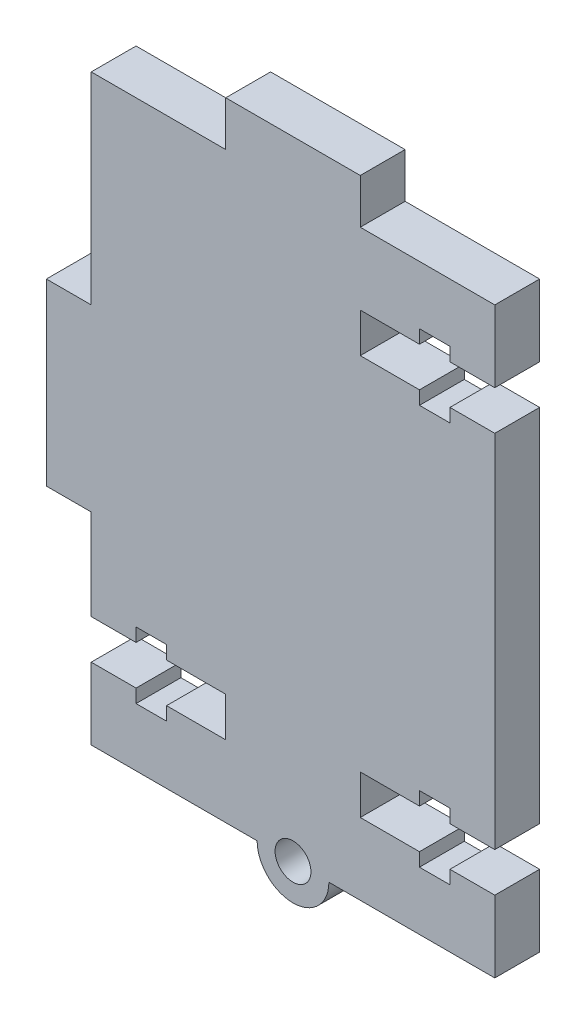
SolidWorks part; units mm, degrees
ref_plane "Front Plane" through (0, 0, 0) normal (0, 0, 1) x (1, 0, 0)
ref_plane "Top Plane" through (0, 0, 0) normal (0, 1, 0) x (1, 0, 0)
ref_plane "Right Plane" through (0, 0, 0) normal (1, 0, 0) x (0, 0, -1)
sketch "Sketch1" plane through (0, 0, 0) normal (0, 0, 1) x (1, 0, 0)
  line L0 (7.5, 32.5) -> (7.5, 37.5)
  line L1 (-22.5, 32.5) -> (-7.5, 32.5)
  line L2 (-22.5, 32.5) -> (-22.5, 10)
  line L3 (-22.5, -32.5) -> (22.5, -32.5)
  line L4 (22.5, 32.5) -> (22.5, -32.5)
  line L5 (7.5, 37.5) -> (-7.5, 37.5)
  line L6 (-7.5, 37.5) -> (-7.5, 32.5)
  line L7 (7.5, 32.5) -> (22.5, 32.5)
  line L8 (-22.5, -10) -> (-22.5, -32.5)
  line L9 (-22.5, 10) -> (-27.5, 10)
  line L11 (-22.5, -10) -> (-27.5, -10)
  line L12 (-27.5, 10) -> (-27.5, -10)
  point P13 (-25, 10)
  dimension "D1" = 45
  dimension "D2" = 65
  dimension "D3" = 22.5
  dimension "D4" = 32.5
  dimension "D5" = 15
  dimension "D6" = 15
  dimension "D7" = 5
  dimension "D8" = 5
  dimension "D9" = 22.5
  dimension "D10" = 20
extrude "Boss-Extrude1" add sketch "Sketch1" along normal blind 5
sketch "Sketch3" plane through (0, 0, 5) normal (0, 0, 1) x (1, 0, 0)
  line L0 (0, 0) -> (28.1265, 0) construction
  line L13 (22.5, -32.5) -> (22.5, 32.5) construction
  line L14 (22.5, 24.5) -> (17.5, 24.5)
  line L15 (17.5, 24.5) -> (17.5, 26)
  line L16 (17.5, 26) -> (14.1, 26)
  line L17 (14.1, 26) -> (14.1, 24.5)
  line L18 (14.1, 24.5) -> (7.5, 24.5)
  line L19 (7.5, 24.5) -> (7.5, 20.1)
  line L20 (7.5, 20.1) -> (14.1, 20.1)
  line L21 (14.1, 20.1) -> (14.1, 18.6)
  line L22 (14.1, 18.6) -> (17.5, 18.6)
  line L23 (17.5, 18.6) -> (17.5, 20.1)
  line L24 (17.5, 20.1) -> (22.5, 20.1)
  line L25 (22.5, 24.5) -> (22.5, 20.1)
  line L26 (-7.5, 32.5) -> (-22.5, 32.5) construction
  line L27 (0, 0) -> (0, 42.4523) construction
  line L28 (22.5, -24.5) -> (22.5, -20.1)
  line L29 (17.5, -20.1) -> (22.5, -20.1)
  line L30 (17.5, -18.6) -> (17.5, -20.1)
  line L31 (14.1, -18.6) -> (17.5, -18.6)
  line L32 (14.1, -20.1) -> (14.1, -18.6)
  line L33 (7.5, -20.1) -> (14.1, -20.1)
  line L34 (7.5, -24.5) -> (7.5, -20.1)
  line L35 (14.1, -24.5) -> (7.5, -24.5)
  line L36 (14.1, -26) -> (14.1, -24.5)
  line L37 (17.5, -26) -> (14.1, -26)
  line L38 (17.5, -24.5) -> (17.5, -26)
  line L39 (22.5, -24.5) -> (17.5, -24.5)
  line L40 (-22.5, -24.5) -> (-17.5, -24.5)
  line L41 (-17.5, -24.5) -> (-17.5, -26)
  line L42 (-17.5, -26) -> (-14.1, -26)
  line L43 (-14.1, -26) -> (-14.1, -24.5)
  line L44 (-14.1, -24.5) -> (-7.5, -24.5)
  line L45 (-7.5, -24.5) -> (-7.5, -20.1)
  line L46 (-7.5, -20.1) -> (-14.1, -20.1)
  line L47 (-14.1, -20.1) -> (-14.1, -18.6)
  line L48 (-14.1, -18.6) -> (-17.5, -18.6)
  line L49 (-17.5, -18.6) -> (-17.5, -20.1)
  line L50 (-17.5, -20.1) -> (-22.5, -20.1)
  line L51 (-22.5, -24.5) -> (-22.5, -20.1)
  dimension "D8" = 4.4
  dimension "D9" = 1.5
  dimension "D10" = 1.5
  dimension "D11" = 3.4
  dimension "D12" = 5
  dimension "D13" = 8
  dimension "D14" = 15
extrude "Cut-Extrude1" cut sketch "Sketch3" against normal blind 5
sketch "Sketch10" plane through (0, 0, 5) normal (0, 0, 1) x (1, 0, 0)
  line L0 (0, 0) -> (0, -37.4843) construction
  line L1 (-22.5, -32.5) -> (22.5, -32.5) construction
  circle A0 centre (0, -32.5) radius 2
  circle A1 centre (0, -32.5) radius 4
  dimension "D1" = 4
  dimension "D2" = 8
extrude "Boss-Extrude3" add sketch "Sketch10" against normal blind 5
sketch "Sketch11" plane through (0, 0, 5) normal (0, 0, 1) x (1, 0, 0)
  line L0 (-2, -32.5) -> (2, -32.5) construction
  circle A0 centre (0, -32.5) radius 2
extrude "Cut-Extrude3" cut sketch "Sketch11" against normal blind 5
